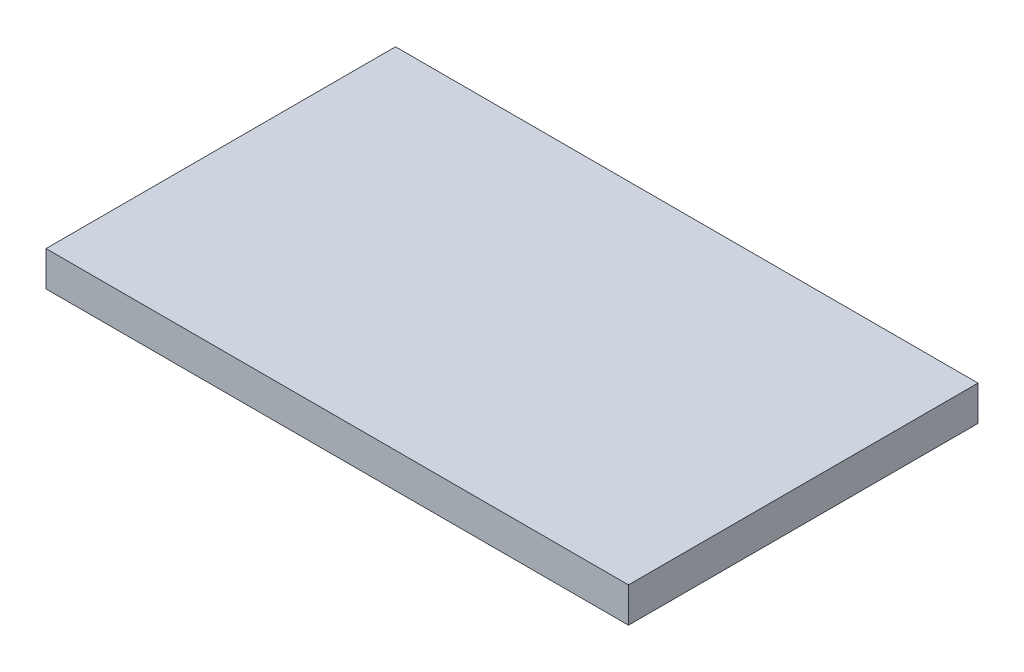
SolidWorks part; units mm, degrees
material "Maple"
ref_plane "Front Plane" through (0, 0, 0) normal (0, 0, 1) x (1, 0, 0)
ref_plane "Top Plane" through (0, 0, 0) normal (0, 1, 0) x (1, 0, 0)
ref_plane "Right Plane" through (0, 0, 0) normal (1, 0, 0) x (0, 0, -1)
sketch "Sketch1" plane through (0, 0, 0) normal (0, 1, 0) x (1, 0, 0)
  line L1 (-250, 150) -> (250, 150)
  line L2 (-250, 150) -> (-250, -150)
  line L3 (-250, -150) -> (250, -150)
  line L4 (250, 150) -> (250, -150)
  line L5 (-250, 150) -> (250, -150) construction
  line L6 (-250, -150) -> (250, 150) construction
  point P0 (0, 0)
  dimension "D1" = 300
  dimension "D2" = 500
extrude "Boss-Extrude1" add sketch "Sketch1" against normal blind 30
